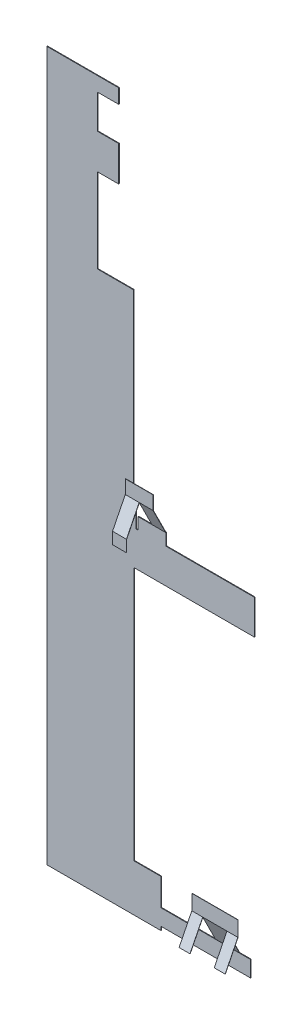
SolidWorks part; units mm, degrees
ref_plane "前视基准面" through (0, 0, 0) normal (0, 0, 1) x (1, 0, 0)
ref_plane "上视基准面" through (0, 0, 0) normal (0, 1, 0) x (1, 0, 0)
ref_plane "右视基准面" through (0, 0, 0) normal (1, 0, 0) x (0, 0, -1)
ref_plane "基准面4"
sketch "草图1" plane through (0, 0, 0) normal (0, 0, 1) x (1, 0, 0)
  line L0 (83.4, -1092.3) -> (83.4, -1117.3)
  line L1 (83.4, -1117.3) -> (98.6, -1117.3)
  line L2 (98.6, -1117.3) -> (98.6, -1092.3)
  line L3 (98.6, -1092.3) -> (83.4, -1092.3)
  line L4 (98.6, -1092.3) -> (98.6, -1117.3)
  line L5 (98.6, -1117.3) -> (114.5, -1117.3)
  line L6 (114.5, -1117.3) -> (114.5, -1092.3)
  line L7 (114.5, -1092.3) -> (98.6, -1092.3)
  line L8 (143.4, -837.8) -> (83.4, -837.8)
  line L9 (83.4, -837.8) -> (83.4, -893.6)
  line L10 (83.4, -893.6) -> (143.4, -893.6)
  line L11 (143.4, -893.6) -> (143.4, -837.8)
  line L12 (0, -782.9) -> (0, -839.5)
  line L13 (0, -839.5) -> (60, -839.5)
  line L14 (60, -839.5) -> (60, -782.9)
  line L15 (60, -782.9) -> (0, -782.9)
  line L16 (0, -276.5) -> (0, -335.9)
  line L17 (0, -335.9) -> (60, -335.9)
  line L18 (60, -335.9) -> (60, -276.5)
  line L19 (60, -276.5) -> (0, -276.5)
  line L20 (188.1, -1163.6) -> (336, -1163.6)
  line L21 (336, -1163.6) -> (336, -1137.1)
  line L22 (336, -1137.1) -> (188.1, -1137.1)
  line L23 (188.1, -1137.1) -> (188.1, -1163.6)
  line L24 (60, -1169.8) -> (60, -1091.2)
  line L25 (60, -1091.2) -> (0, -1091.2)
  line L26 (0, -1091.2) -> (0, -1169.8)
  line L27 (0, -1169.8) -> (60, -1169.8)
  line L28 (0, 0) -> (0, -80.6)
  line L29 (0, -80.6) -> (60, -80.6)
  line L30 (60, -80.6) -> (60, 0)
  line L31 (60, 0) -> (0, 0)
  line L32 (143.4, -673.2) -> (83.4, -673.2)
  line L33 (83.4, -673.2) -> (83.4, -754.3)
  line L34 (83.4, -754.3) -> (143.4, -754.3)
  line L35 (143.4, -754.3) -> (143.4, -673.2)
  line L36 (142.9, -379.5) -> (83.4, -379.5)
  line L37 (83.4, -379.5) -> (83.4, -463)
  line L38 (83.4, -463) -> (142.9, -463)
  line L39 (142.9, -463) -> (142.9, -379.5)
  line L40 (0, -1007.7) -> (0, -1091.2)
  line L41 (0, -1091.2) -> (60, -1091.2)
  line L42 (60, -1091.2) -> (60, -1007.7)
  line L43 (60, -1007.7) -> (0, -1007.7)
  line L44 (83.4, -754.3) -> (83.4, -837.8)
  line L45 (83.4, -837.8) -> (143.4, -837.8)
  line L46 (143.4, -837.8) -> (143.4, -754.3)
  line L47 (143.4, -754.3) -> (83.4, -754.3)
  line L48 (0, -923.6) -> (0, -1007.7)
  line L49 (0, -1007.7) -> (60, -1007.7)
  line L50 (60, -1007.7) -> (60, -923.6)
  line L51 (60, -923.6) -> (0, -923.6)
  line L52 (0, -839.5) -> (0, -923.6)
  line L53 (0, -923.6) -> (60, -923.6)
  line L54 (60, -923.6) -> (60, -839.5)
  line L55 (60, -839.5) -> (0, -839.5)
  line L56 (0, -191.9) -> (0, -276.5)
  line L57 (0, -276.5) -> (60, -276.5)
  line L58 (60, -276.5) -> (60, -191.9)
  line L59 (60, -191.9) -> (0, -191.9)
  line L60 (0, -335.9) -> (0, -420.6)
  line L61 (0, -420.6) -> (60, -420.6)
  line L62 (60, -420.6) -> (60, -335.9)
  line L63 (60, -335.9) -> (0, -335.9)
  line L64 (83.4, -893.6) -> (83.4, -978.3)
  line L65 (83.4, -978.3) -> (143.4, -978.3)
  line L66 (143.4, -978.3) -> (143.4, -893.6)
  line L67 (143.4, -893.6) -> (83.4, -893.6)
  line L68 (83.4, -276.5) -> (83.4, -379.5)
  line L69 (83.4, -379.5) -> (142.9, -379.5)
  line L70 (142.9, -379.5) -> (142.9, -276.5)
  line L71 (142.9, -276.5) -> (83.4, -276.5)
  line L72 (142.9, -463) -> (83.4, -463)
  line L73 (83.4, -463) -> (83.4, -566.2)
  line L74 (83.4, -566.2) -> (142.9, -566.2)
  line L75 (142.9, -566.2) -> (142.9, -463)
  line L76 (0, -677.8) -> (0, -782.9)
  line L77 (0, -782.9) -> (60, -782.9)
  line L78 (60, -782.9) -> (60, -677.8)
  line L79 (60, -677.8) -> (0, -677.8)
  line L80 (0, -80.6) -> (0, -191.9)
  line L81 (0, -191.9) -> (60, -191.9)
  line L82 (60, -191.9) -> (60, -80.6)
  line L83 (60, -80.6) -> (0, -80.6)
  line L84 (83.4, -1092.3) -> (98.6, -1092.3)
  line L85 (98.6, -1092.3) -> (114.5, -1092.3)
  line L86 (114.5, -1092.3) -> (143.4, -1092.3)
  line L87 (143.4, -1092.3) -> (143.4, -978.3)
  line L88 (143.4, -978.3) -> (83.4, -978.3)
  line L89 (83.4, -978.3) -> (83.4, -1092.3)
  line L90 (0, -550.6) -> (0, -677.8)
  line L91 (0, -677.8) -> (60, -677.8)
  line L92 (60, -677.8) -> (60, -550.6)
  line L93 (60, -550.6) -> (0, -550.6)
  line L94 (0, -420.6) -> (0, -550.6)
  line L95 (0, -550.6) -> (60, -550.6)
  line L96 (60, -550.6) -> (60, -420.6)
  line L97 (60, -420.6) -> (0, -420.6)
  line L98 (166.2, -1092.3) -> (143.4, -1092.3)
  line L99 (143.4, -1092.3) -> (114.5, -1092.3)
  line L100 (114.5, -1092.3) -> (114.5, -1117.3)
  line L101 (114.5, -1117.3) -> (98.6, -1117.3)
  line L102 (98.6, -1117.3) -> (83.4, -1117.3)
  line L103 (83.4, -1117.3) -> (83.4, -1092.3)
  line L104 (83.4, -1092.3) -> (83.4, -978.3)
  line L105 (83.4, -978.3) -> (83.4, -893.6)
  line L106 (83.4, -893.6) -> (83.4, -837.8)
  line L107 (83.4, -837.8) -> (83.4, -754.3)
  line L108 (83.4, -754.3) -> (83.4, -673.2)
  line L109 (83.4, -673.2) -> (143.4, -673.2)
  line L110 (143.4, -673.2) -> (342.5, -673.2)
  line L111 (342.5, -673.2) -> (342.5, -616.2)
  line L112 (342.5, -616.2) -> (192.5, -616.2)
  line L113 (192.5, -616.2) -> (146.7, -616.2)
  line L114 (146.7, -616.2) -> (146.7, -566.2)
  line L115 (146.7, -566.2) -> (142.9, -566.2)
  line L116 (142.9, -566.2) -> (83.4, -566.2)
  line L117 (83.4, -566.2) -> (83.4, -463)
  line L118 (83.4, -463) -> (83.4, -379.5)
  line L119 (83.4, -379.5) -> (83.4, -276.5)
  line L120 (83.4, -276.5) -> (83.4, -137.6)
  line L121 (83.4, -137.6) -> (118.4, -137.6)
  line L122 (118.4, -137.6) -> (118.4, -79.7)
  line L123 (118.4, -79.7) -> (83.4, -79.7)
  line L124 (83.4, -79.7) -> (83.4, -23.7)
  line L125 (83.4, -23.7) -> (118.4, -23.7)
  line L126 (118.4, -23.7) -> (118.4, 0)
  line L127 (118.4, 0) -> (60, 0)
  line L128 (60, 0) -> (60, -80.6)
  line L129 (60, -80.6) -> (60, -191.9)
  line L130 (60, -191.9) -> (60, -276.5)
  line L131 (60, -276.5) -> (60, -335.9)
  line L132 (60, -335.9) -> (60, -420.6)
  line L133 (60, -420.6) -> (60, -550.6)
  line L134 (60, -550.6) -> (60, -677.8)
  line L135 (60, -677.8) -> (60, -782.9)
  line L136 (60, -782.9) -> (60, -839.5)
  line L137 (60, -839.5) -> (60, -923.6)
  line L138 (60, -923.6) -> (60, -1007.7)
  line L139 (60, -1007.7) -> (60, -1091.2)
  line L140 (60, -1091.2) -> (60, -1169.8)
  line L141 (60, -1169.8) -> (188.1, -1169.8)
  line L142 (188.1, -1169.8) -> (188.1, -1163.6)
  line L143 (188.1, -1163.6) -> (188.1, -1137.1)
  line L144 (188.1, -1137.1) -> (188.1, -1117.3)
  line L145 (188.1, -1117.3) -> (188.1, -1092.3)
  line L146 (188.1, -1092.3) -> (166.2, -1092.3)
  dimension "D1" = 60
  dimension "D2" = 80.6
  dimension "D3" = 111.3
  dimension "D4" = 84.6
  dimension "D5" = 59.4
  dimension "D6" = 84.7
  dimension "D7" = 130
  dimension "D8" = 127.2
  dimension "D9" = 105.1
  dimension "D10" = 56.6
  dimension "D11" = 84.1
  dimension "D12" = 84.1
  dimension "D13" = 83.5
  dimension "D14" = 78.6
  dimension "D15" = 58.4
  dimension "D16" = 23.7
  dimension "D17" = 35
  dimension "D18" = 56
  dimension "D19" = 57.9
  dimension "D20" = 35
  dimension "D21" = 138.9
  dimension "D22" = 59.5
  dimension "D23" = 103
  dimension "D24" = 83.5
  dimension "D25" = 103.2
  dimension "D26" = 59.5
  dimension "D27" = 3.8
  dimension "D28" = 50
  dimension "D29" = 45.8
  dimension "D30" = 150
  dimension "D31" = 57
  dimension "D32" = 199.1
  dimension "D33" = 60
  dimension "D34" = 81.1
  dimension "D35" = 83.5
  dimension "D36" = 55.8
  dimension "D37" = 84.7
  dimension "D38" = 90
  dimension "D39" = 128.1
  dimension "D40" = 15.2
  dimension "D41" = 15.9
  dimension "D42" = 147.9
  dimension "D43" = 6.2
  dimension "D44" = 26.5
extrude "拉伸1" add sketch "草图1" against normal blind 1 contours L2 L3 L0 L1 | L6 L7 L2 L5 | L10 L11 L8 L9 | L14 L15 L12 L13 | L18 L19 L16 L17 | L22 L23 L20 L21 | L26 L27 L24 L25 | L30 L31 L28 L29 | L34 L35 L32 L33 | L38 L39 L36 L37 | L42 L43 L40 L25 | L8 L46 L34 L44 | L50 L51 L48 L43 | L51 L54 L13 L52 | L58 L59 L56 L19 | L61 L62 L17 L60 | L65 L66 L10 L64 | L70 L71 L68 L36 | L74 L75 L38 L73 | L78 L79 L76 L15 | L59 L82 L29 L80 | L65 L89 L3 L7 L86 L87 | L92 L93 L90 L79 | L93 L96 L61 L94 | L145 L146 L98 L86 L6 L5 L1 L0 L89 L64 L9 L44 L33 L32 L110 L111 L112 L113 L114 L115 L74 L73 L37 L68 L120 L121 L122 L123 L124 L125 L126 L127 L30 L82 L58 L18 L62 L96 L92 L78 L14 L54 L50 L42 L24 L141 L142 L23 L144
sketch "草图2" plane through (0, 0, 0) normal (0, 0, 1) x (1, 0, 0)
  line L0 (150.3, -616.2) -> (150.3, -596.9)
  line L1 (150.3, -596.9) -> (196.1, -596.9)
  line L2 (196.1, -596.9) -> (196.1, -616.2)
  line L3 (196.1, -616.2) -> (150.3, -616.2)
  dimension "D1" = 19.3
  dimension "D2" = 45.8
extrude "拉伸2" add sketch "草图2" against normal up to surface (1 mm away) up to face at (157.6083, -577.9917, -1)
ref_plane "基准面5" through (173.2, -616.2, 0) normal (1, 0, 0) x (0, 0, -1)
sketch "草图3" plane through (173.2, -616.2, 0) normal (1, 0, 0) x (0, 0, -1)
  line L0 (-20.5, 61.3) -> (-20.5429, 83.8)
  line L1 (-20.5429, 83.8) -> (-21.0429, 83.8)
  line L2 (-21.0429, 83.8) -> (-21, 61.3)
  line L3 (-21, 61.3) -> (-20.5, 61.3)
  line L4 (0.5, 19.3) -> (-20.5, 61.3)
  line L5 (-20.5, 61.3) -> (-21, 61.3)
  line L6 (-21, 61.3) -> (0, 19.3)
  line L7 (0, 19.3) -> (0.5, 19.3)
  line L8 (1, 19.3) -> (0, 19.3) construction
  line L9 (1, 19.3) -> (0, 19.3) construction
  dimension "D1" = 42
  dimension "D2" = 0.5
  dimension "D3" = 0.5
  dimension "D4" = 22.5
extrude "拉伸3" add sketch "草图3" against normal up to surface contours L2 L3 L0 L1 | L6 L7 L4 L3
ref_plane "基准面6" through (173.2, -616.2, 0) normal (1, 0, 0) x (0, 0, -1)
sketch "草图4" plane through (173.2, -616.2, 0) normal (1, 0, 0) x (0, 0, -1)
  line L0 (-20.5, 61.3) -> (-20.5, 83.8)
  line L1 (-20.5, 83.8) -> (-21.0429, 83.8)
  line L2 (-21.0429, 83.8) -> (-21, 61.3)
  line L3 (-21, 61.3) -> (-20.5, 61.3)
  dimension "D1" = 22.5
extrude "拉伸4" add sketch "草图4" against normal up to surface (22.9 mm away) up to face at (150.3, -606.55, -0.5)
ref_plane "基准面7" through (318, -1163.6, 0) normal (1, 0, 0) x (0, 0, -1)
sketch "草图6" plane through (318, -1163.6, 0) normal (1, 0, 0) x (0, 0, -1)
  line L0 (-20.5, 68.5) -> (-20.5, 93.5)
  line L1 (-20.5, 93.5) -> (-20.9, 93.5)
  line L2 (-20.9, 93.5) -> (-20.9, 68.5)
  line L3 (-20.9, 68.5) -> (-20.5, 68.5)
  line L4 (0.5, 26.5) -> (-20.5, 68.5)
  line L5 (-20.5, 68.5) -> (-20.9, 68.5)
  line L6 (-20.9, 68.5) -> (0.1, 26.5)
  line L7 (0.1, 26.5) -> (0.5, 26.5)
  dimension "D1" = 46.9574
  dimension "D2" = 46.9574
  dimension "D3" = 0.4
  dimension "D4" = 25
  dimension "D5" = 0.4
extrude "拉伸6" add sketch "草图6" against normal blind 40 contours L2 L3 L0 L1 | L6 L7 L4 L3
ref_plane "基准面8" through (318, -1163.6, 0) normal (1, 0, 0) x (0, 0, -1)
sketch "草图7" plane through (318, -1163.6, 0) normal (1, 0, 0) x (0, 0, -1)
  line L0 (-20.9, 93.5) -> (-20.9, 68.5)
  line L1 (-20.9, 68.5) -> (-20.5, 68.5)
  line L2 (-20.5, 68.5) -> (-20.5, 93.5)
  line L3 (-20.5, 93.5) -> (-20.9, 93.5)
  line L4 (-20.5, 68.5) -> (-20.9, 68.5)
  line L5 (-20.9, 68.5) -> (-41.9, 26.5)
  line L6 (-41.9, 26.5) -> (-41.5, 26.5)
  line L7 (-41.5, 26.5) -> (-20.5, 68.5)
  dimension "D1" = 46.9574
  dimension "D2" = 46.9574
extrude "拉伸7" add sketch "草图7" along normal blind 18 contours L2 L3 L0 L1 | L6 L7 L1 L5
ref_plane "基准面9" through (298, -1163.6, 0) normal (1, 0, 0) x (0, 0, -1)
mirror "镜像1" about plane through (298, -1163.6, 0) normal (1, 0, 0) of "拉伸7"
sketch "草图9" plane through (150.3, 0, 0) normal (-1, 0, 0) x (0, 0, 1)
  line L0 (21, -554.9) -> (20.5, -554.9) construction
  line L1 (21, -554.9) -> (20.5, -554.9)
  line L2 (20.75, -554.9) -> (41.75, -596.9) construction
  line L3 (21, -554.9) -> (42, -596.9)
  line L4 (42, -596.9) -> (42, -616.2)
  line L5 (20.5, -554.9) -> (41.5, -596.9)
  line L6 (41.5, -596.9) -> (41.5, -616.2)
  line L7 (42, -596.9) -> (41.5, -596.9) construction
  line L8 (42, -616.2) -> (41.5, -616.2)
  dimension "D1" = 42
  dimension "D2" = 21
  dimension "D3" = 19.3
extrude "凸台-拉伸720" add sketch "草图9" against normal up to surface (22.9 mm away) up to face at (173.2, -575.9, 10.25)
